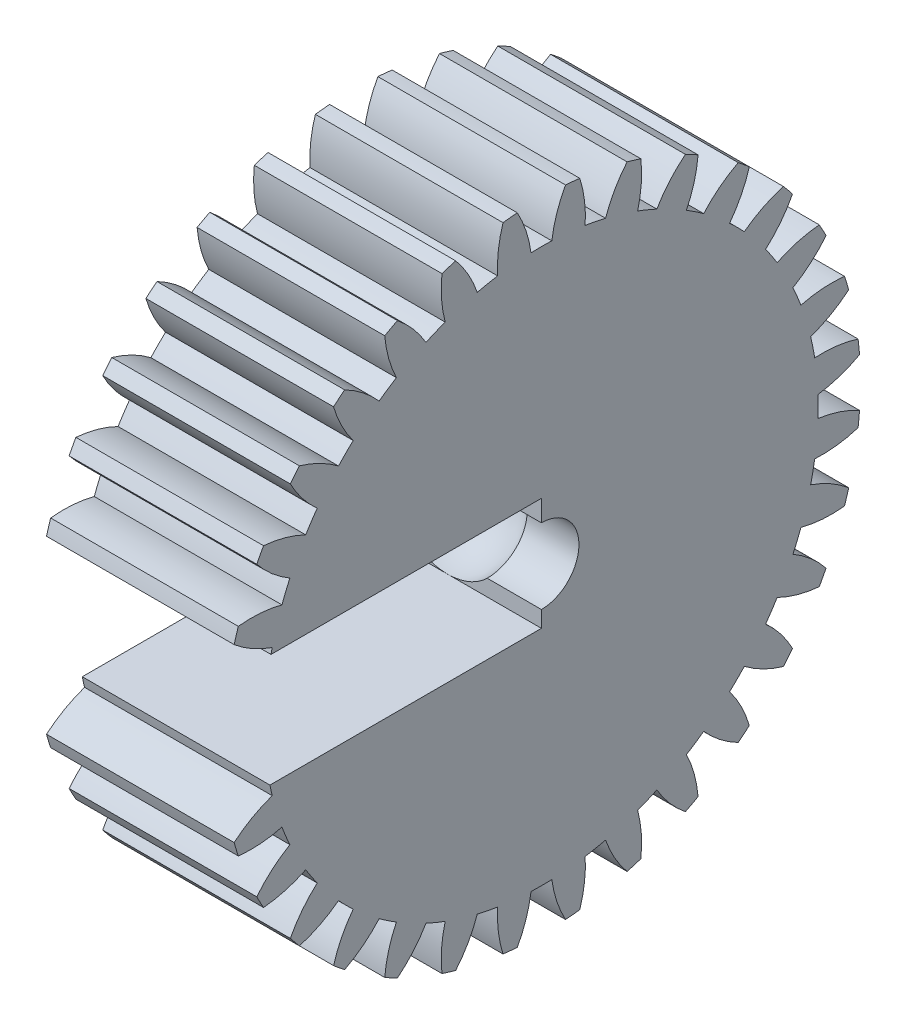
SolidWorks part; units mm, degrees
ref_plane "Plane1" through (0, 0, 0) normal (0, 0, 1) x (1, 0, 0)
ref_plane "Plane2" through (0, 0, 0) normal (0, 1, 0) x (1, 0, 0)
ref_plane "Plane3" through (0, 0, 0) normal (1, 0, 0) x (0, 0, -1)
other "Configuration Table"
sketch "HoldingSke" plane through (0, 0, 0) normal (0, 1, 0) x (1, 0, 0)
  line L0 (0, 0) -> (1.6961, -1.0598)
  line L1 (-15, 0) -> (100, 0) construction
  line L2 (0, 0) -> (-2.1039, 2.3779)
  line L3 (0, 0) -> (-11.863, 4.5341)
  line L4 (0, 0) -> (7.3237, 4.5764)
  line L5 (0, 0) -> (-46.8476, -17.4728)
  line L6 (0, 0) -> (-4.1448, -2.7965)
  line L7 (-2.1039, 2.3779) -> (8.6586, 51.2059)
  line L8 (-76.2, 54.61) -> (-75.9, 54.61)
  line L9 (-67.7845, 28.3722) -> (-49.3413, 33.142)
  line L10 (-76.2, 71.12) -> (104.1128, 71.12)
  line L11 (0, 0) -> (-5, 0)
  line L12 (-76.2, 101.6) -> (-76.181, 101.6)
  line L13 (24.9733, 27.94) -> (52.9518, 28.4284)
  line L14 (24.9733, 27.94) -> (24.9743, 27.94)
  line L15 (24.9733, 27.94) -> (100.4006, 29.5858)
  line L16 (-63.627, -0.5) -> (-12.827, -0.5)
  circle A0 centre (0, 0) radius 1
  circle A1 centre (0, 0) radius 7.374
  circle A2 centre (0, 0) radius 37.5
  circle A3 centre (0, 0) radius 1
  dimension "MHD" = 14.748
  dimension "Hub_dia" = 75
  dimension "Bore" = 2
  dimension "MBD" = 2
  dimension "Num_teeth" = 32
  dimension "Pitch" = 2
  dimension "Overall_len" = 50
  dimension "Show_teeth" = 32
  dimension "Thickness" = 5
  dimension "OAL" = 50.0001
  dimension "T_dim" = 0.3
  dimension "Ap" = 14.5
  dimension "H" = 19.05
  dimension "Pitch_radius" = 180.3128
  dimension "Width" = 5
  dimension "Backlash" = 0.019
  dimension "Addendum_fac" = 1
  dimension "Dedendum_fac" = 1.25
  dimension "Clearance_fac" = 0.25
  dimension "Dedendum_add" = 0.001
  dimension "Module" = 0.5
sketch "BasProSke" plane through (0, 0, 0) normal (0, 1, 0) x (1, 0, 0)
  line L0 (-10, 0) -> (60, 0) construction
  line L1 (0, 0) -> (0, 8.5)
  line L2 (0, 0) -> (5, 0)
  line L3 (5, 0) -> (5, 8.5)
  line L4 (5, 8.5) -> (0, 8.5)
  dimension "Thickness" = 5
  dimension "Diameter" = 17
revolve "Base-Revolve" add sketch "BasProSke" angle 360 about L0
sketch "TooCutSke" plane through (0, 0, 0) normal (1, 0, 0) x (0, 0, -1)
  line L1 (0, 0) -> (0, 107) construction
  line L2 (0, 0) -> (-0.4258, 7.9887) construction
  line L3 (0, 0) -> (-1.5667, 15.9069) construction
  line L4 (-0.4258, 7.9887) -> (-0.7833, 7.9534) construction
  arc A0 (0.277, 7.3688) -> (-0.277, 7.3688) centre (0, 0) ccw
  arc A1 (0.6561, 8.5001) -> (-0.6561, 8.5001) centre (0, 0) ccw
  circle A2 centre (0, 0) radius 8 construction
  circle A3 centre (0, 0) radius 7.7452 construction
  arc A4 (-0.277, 7.3688) -> (-0.6561, 8.5001) centre (-3.4475, 6.9356) ccw
  arc A5 (0.6561, 8.5001) -> (0.277, 7.3688) centre (3.4475, 6.9356) ccw
  dimension "Root_dia" = 14.748
  dimension "Overcut_dia" = 17.0508
  dimension "Pitch_dia" = 16
  dimension "Base_dia" = 15.4904
  dimension "Flank_rad" = 3.2
  dimension "Half_ang" = 5.625
  dimension "Half_CT" = 0.3593
extrude "ToothCut" cut sketch "TooCutSke" along normal through all
fillet "Breaks" [suppressed] radius 0.01
fillet "RootFillets" [suppressed] radius 0.126
pattern_circular "TeethCuts" count 32 every 11.25 about axis through (-10, 0, 0) along (1, 0, 0) of "ToothCut", "RootFillets", "Breaks"
sketch "HubNeaOneSke" plane through (0, 0, 0) normal (-1, 0, 0) x (0, 0, 1)
  circle A0 centre (0, 0) radius 7.374
  dimension "Diameter" = 14.748
extrude "HubNearOne" [suppressed] add sketch "HubNeaOneSke" along normal blind 45.0001
sketch "HubNeaBotSke" plane through (0, 0, 0) normal (-1, 0, 0) x (0, 0, 1)
  circle A0 centre (0, 0) radius 7.374
  dimension "Diameter" = 14.748
extrude "HubNearBoth" [suppressed] add sketch "HubNeaBotSke" along normal blind 22.5
ref_plane "FarPln" through (5, 0, 0) normal (1, 0, 0) x (0, 0, -1)
sketch "HubFarSke" plane through (5, 0, 0) normal (1, 0, 0) x (0, 0, -1)
  circle A0 centre (0, 0) radius 7.374
  dimension "Diameter" = 14.748
extrude "HubFar" [suppressed] add sketch "HubFarSke" along normal blind 22.5
sketch "BorSke" plane through (0, 0, 0) normal (1, 0, 0) x (0, 0, -1)
  circle A0 centre (0, 0) radius 1
  dimension "Diameter" = 2
extrude "Bore" cut sketch "BorSke" along normal mid plane 100.0001
sketch "KeySke" plane through (0, 0, 0) normal (1, 0, 0) x (0, 0, -1)
  line L0 (-0.4, 0) -> (-0.4, 1.3)
  line L1 (-0.4, 1.3) -> (0.4, 1.3)
  line L2 (0.4, 1.3) -> (0.4, 0)
  line L3 (0, 0) -> (0, 34) construction
  line L4 (-0.4, 0) -> (0.4, 0)
  dimension "Offset" = 1.3
  dimension "Width" = 0.8
extrude "Keyway" [suppressed] cut sketch "KeySke" along normal mid plane 100.0001
pattern_circular "Keyway2" [suppressed] count 2 every 90 about axis through (-10, 0, 0) along (1, 0, 0)
sketch "Sketch1" plane through (5, 0, 0) normal (1, 0, 0) x (0, 0, -1)
  line L4 (0, 1.5656) -> (0, -1.4344)
  line L5 (0, -1.4344) -> (-10, -1.4344)
  line L6 (-10, -1.4344) -> (-10, 1.5656)
  line L7 (-10, 1.5656) -> (0, 1.5656)
  dimension "D1" = 10
  dimension "D2" = 10
  dimension "D3" = 3
  dimension "D4" = 3
extrude "Cut-Extrude1" cut sketch "Sketch1" against normal through all both
ref_plane "Plane5" through (0, 0.0656, 0) normal (0, 1, 0) x (1, 0, 0)
sketch "Sketch7" plane through (0, 0.0656, 0) normal (0, 1, 0) x (1, 0, 0)
  line L1 (4, 0) -> (1, 0)
  arc A1 (1, 0) -> (4, 0) centre (2.5, 0) cw
  dimension "D2" = 3
  dimension "D1" = 1.5
  dimension "D3" = 1
revolve "Cut-Revolve2" cut sketch "Sketch7" angle 360 about L1
equation "' \"Module@HoldingSke\" = 6.35"
equation "' \"Num_teeth@HoldingSke\" = 12"
equation "' \"Ap@HoldingSke\" =  20"
equation "' \"Ap@HoldingSke\" = 20"
equation "' \"Width@HoldingSke\" = 0.5 * 25.4"
equation "' \"Hub_dia@HoldingSke\"= 1 * 25.4"
equation "' \"Hub_dia@HoldingSke\" = 1 * 25.4"
equation "' \"Overall_len@HoldingSke\" = 1.0 * 25.4"
equation "' \"Bore@HoldingSke\" = 0.75 * 25.4"
equation "' \"T_dim@HoldingSke\" = 0.1 * 25.4"
equation "' \"Width@KeySke\" = 0.25 * 25.4"
equation "' \"Show_teeth@HoldingSke\" = 13"
equation "' \"Backlash@HoldingSke\" = 0.009 * 25.4"
equation "' \"Addendum_fac@HoldingSke\" = 1.0"
equation "' \"Dedendum_fac@HoldingSke\" = 1.25"
equation "' \"Dedendum_add@HoldingSke\" = 0.00005 * 25.4"
equation "' \"Clearance_fac@HoldingSke\" = 0.25"
equation "\"Pitch@HoldingSke\" = 1 / \"Module@HoldingSke\""
equation "\"Overcut_dia@TooCutSke\" = (\"Num_teeth@HoldingSke\" + 2 * \"Addendum_fac@HoldingSke\") / \"Pitch@HoldingSke\" + 0.002 * 25.4"
equation "\"Pitch_dia@TooCutSke\" = \"Num_teeth@HoldingSke\" / \"Pitch@HoldingSke\""
equation "\"Base_dia@TooCutSke\" = \"Num_teeth@HoldingSke\" / \"Pitch@HoldingSke\" * cos((\"Ap@HoldingSke\"  * 3.14159265 / 180))"
equation "\"Root_dia@TooCutSke\" = (\"Num_teeth@HoldingSke\" + 2) / \"Pitch@HoldingSke\" - 2 * (\"Addendum_fac@HoldingSke\" + \"Dedendum_fac@HoldingSke\") / \"Pitch@HoldingSke\" - \"Dedendum_add@HoldingSke\" * 2"
equation "\"Half_ang@TooCutSke\" = 180 / \"Num_teeth@HoldingSke\""
equation "\"Half_CT@TooCutSke\" = \"Num_teeth@HoldingSke\" / \"Pitch@HoldingSke\" * sin((3.14159265 / 2 / \"Num_teeth@HoldingSke\")) / 2 - 7 * \"Backlash@HoldingSke\" / 4"
equation "\"Flank_rad@TooCutSke\" = \"Num_teeth@HoldingSke\" / \"Pitch@HoldingSke\" / 5"
equation "\"Radius@RootFillets\" = \"Clearance_fac@HoldingSke\" / \"Pitch@HoldingSke\" + \"Dedendum_add@HoldingSke\""
equation "\"Break_rad@Breaks\" = 0.02 / \"Pitch@HoldingSke\""
equation "\"Thickness@HoldingSke\" = \"Width@HoldingSke\""
equation "\"OAL@HoldingSke\" = \"Thickness@HoldingSke\""
equation "\"MHD@HoldingSke\" = (\"Num_teeth@HoldingSke\" + 2) / \"Pitch@HoldingSke\" - 2 * (\"Addendum_fac@HoldingSke\" + \"Dedendum_fac@HoldingSke\")  / \"Pitch@HoldingSke\" - \"Dedendum_add@HoldingSke\" * 2"
equation "\"MBD@HoldingSke\" = (\"Num_teeth@HoldingSke\" + 2) / \"Pitch@HoldingSke\" - 2 * (\"Addendum_fac@HoldingSke\" + \"Dedendum_fac@HoldingSke\")  / \"Pitch@HoldingSke\" - \"Dedendum_add@HoldingSke\" * 2 - 0.002 * 25.4"
equation "\"MHD@HoldingSke\" = ((sgn( \"MHD@HoldingSke\" - \"Hub_dia@HoldingSke\" )-1)*( \"MHD@HoldingSke\" - \"Hub_dia@HoldingSke\" ))/-2+ \"Hub_dia@HoldingSke\""
equation "\"MBD@HoldingSke\" = ((sgn( \"MBD@HoldingSke\" - \"Bore@HoldingSke\" )-1)*( \"MBD@HoldingSke\" - \"Bore@HoldingSke\" ))/-2+ \"Bore@HoldingSke\""
equation "\"OAL@HoldingSke\" = ((sgn( \"OAL@HoldingSke\" - \"Overall_len@HoldingSke\" )+1)*( \"OAL@HoldingSke\" - \"Overall_len@HoldingSke\" ))/2 + \"Overall_len@HoldingSke\" + 0.000002 * 25.4"
equation "\"Num_teeth@TeethCuts\" = int( \"Show_teeth@HoldingSke\" ) + 1"
equation "\"Num_teeth@TeethCuts\" = ((sgn( \"Num_teeth@TeethCuts\" - \"Num_teeth@HoldingSke\" )-1)*( \"Num_teeth@TeethCuts\" - \"Num_teeth@HoldingSke\" ))/-2+ \"Num_teeth@HoldingSke\""
equation "\"Num_teeth@TeethCuts\" = ((sgn( \"Num_teeth@TeethCuts\" - 2.0)+1)*( \"Num_teeth@TeethCuts\" - 2.0))/2 +2.0"
equation "\"Angle@TeethCuts\" = 360.0 / \"Num_teeth@HoldingSke\""
equation "\"Diameter@BasProSke\" = (\"Num_teeth@HoldingSke\" + 2 * \"Addendum_fac@HoldingSke\") / \"Pitch@HoldingSke\""
equation "\"Thickness@BasProSke\"  = \"Thickness@HoldingSke\""
equation "' \"Fillet_rad@BasProSke\" =  \"Thickness@HoldingSke\" * 0.05"
equation "' \"Fillet_rad@BasProSke\" = \"Thickness@HoldingSke\" * 0.05"
equation "\"MHD@HoldingSke\" = ((sgn( \"MHD@HoldingSke\" - \"Root_dia@TooCutSke\" )-1)*( \"MHD@HoldingSke\" - \"Root_dia@TooCutSke\" ))/-2+ \"Root_dia@TooCutSke\""
equation "\"Diameter@HubNeaOneSke\" = \"MHD@HoldingSke\""
equation "\"Length@HubNearOne\" = \"OAL@HoldingSke\" - \"Thickness@BasProSke\""
equation "\"Diameter@HubNeaBotSke\" = \"MHD@HoldingSke\""
equation "\"Length@HubNearBoth\" = ( \"OAL@HoldingSke\" - \"Thickness@BasProSke\" ) / 2.0"
equation "\"Thickness@FarPln\" = \"Thickness@BasProSke\""
equation "\"Diameter@HubFarSke\" = \"MHD@HoldingSke\""
equation "\"Length@HubFar\" = ( \"OAL@HoldingSke\" - \"Thickness@BasProSke\" ) / 2.0"
equation "\"Diameter@BorSke\" = \"MBD@HoldingSke\""
equation "\"D1@Bore\" = \"OAL@HoldingSke\" * 2.0"
equation "\"D1@Keyway\" = \"OAL@HoldingSke\" * 2.0"
equation "\"Offset@KeySke\" = \"T_dim@HoldingSke\" + \"MBD@HoldingSke\" / 2.0"
